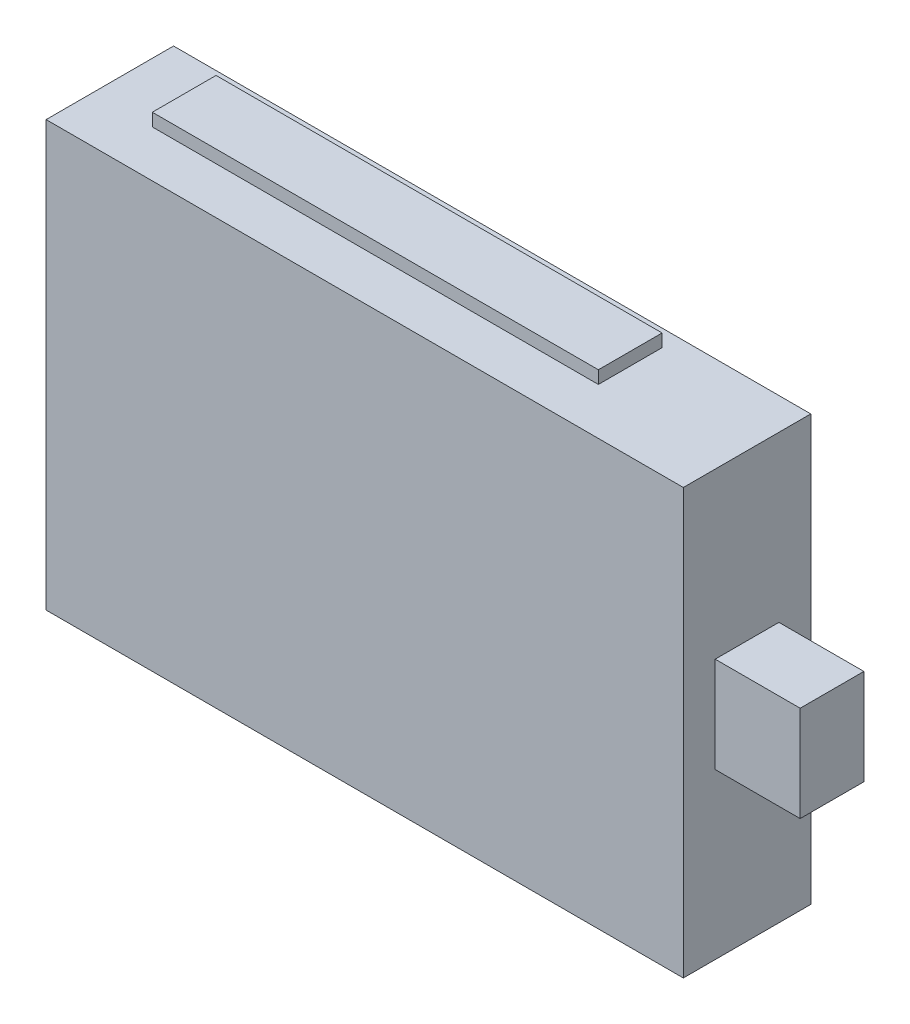
SolidWorks part; units mm, degrees
ref_plane "前视基准面" through (0, 0, 0) normal (0, 0, 1) x (1, 0, 0)
ref_plane "上视基准面" through (0, 0, 0) normal (0, 1, 0) x (1, 0, 0)
ref_plane "右视基准面" through (0, 0, 0) normal (1, 0, 0) x (0, 0, -1)
other "Configuration Table"
sketch "草图1" plane through (0, 0, 0) normal (0, 0, 1) x (1, 0, 0)
  line L1 (-30, -20) -> (30, -20)
  line L2 (-30, -20) -> (-30, 20)
  line L3 (-30, 20) -> (30, 20)
  line L4 (30, -20) -> (30, 20)
  line L5 (-30, -20) -> (30, 20) construction
  line L6 (-30, 20) -> (30, -20) construction
  point P0 (0, 0)
extrude "5V battery / power bank envelope - 60 x 40 x 12 mm" add sketch "草图1" along normal blind 12 from offset 6 separate body
sketch "草图2" plane through (0, 0, 0) normal (0, 0, 1) x (1, 0, 0)
  line L1 (30, -4.5) -> (38, -4.5)
  line L2 (30, -4.5) -> (30, 4.5)
  line L3 (30, 4.5) -> (38, 4.5)
  line L4 (38, -4.5) -> (38, 4.5)
  line L5 (30, -4.5) -> (38, 4.5) construction
  line L6 (30, 4.5) -> (38, -4.5) construction
  point P0 (34, 0)
extrude "USB power cable clearance marker" add sketch "草图2" along normal blind 6 from offset 3 separate body
sketch "草图3" plane through (0, 0, 0) normal (0, 0, 1) x (1, 0, 0)
  line L1 (-21, 23.4) -> (21, 23.4)
  line L2 (-21, 23.4) -> (-21, 24.6)
  line L3 (-21, 24.6) -> (21, 24.6)
  line L4 (21, 23.4) -> (21, 24.6)
  line L5 (-21, 23.4) -> (21, 24.6) construction
  line L6 (-21, 24.6) -> (21, 23.4) construction
  point P0 (0, 24)
extrude "power label plate - 5V POWER" add sketch "草图3" along normal blind 6 from offset 1 separate body
